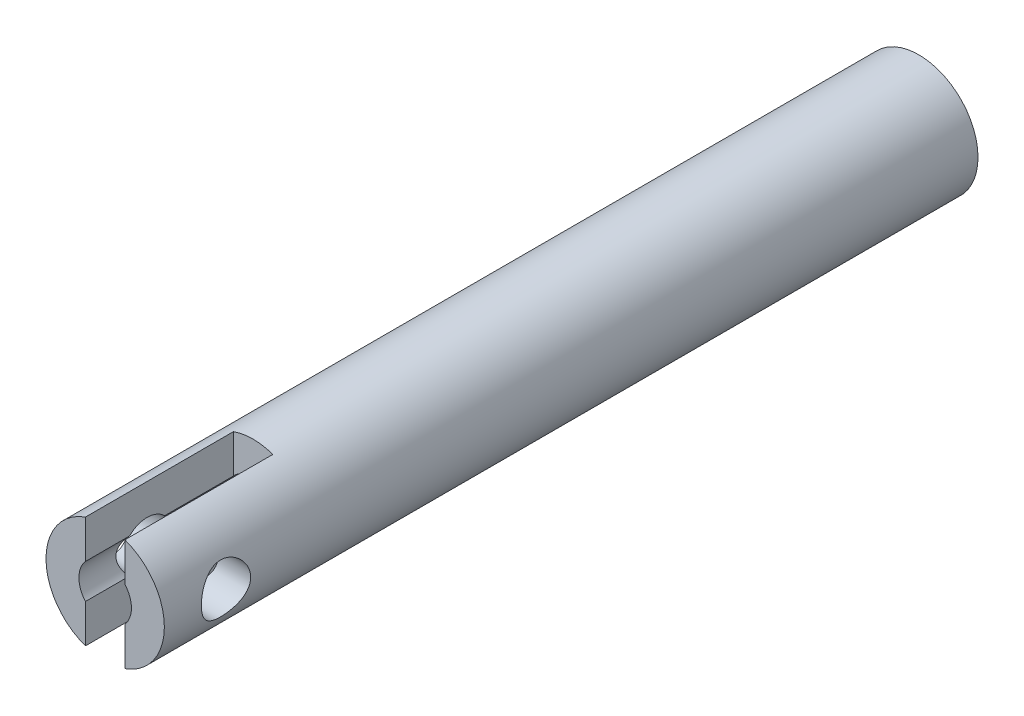
SolidWorks part; units mm, degrees
ref_plane "Front Plane" through (0, 0, 0) normal (0, 0, 1) x (1, 0, 0)
ref_plane "Top Plane" through (0, 0, 0) normal (0, 1, 0) x (1, 0, 0)
ref_plane "Right Plane" through (0, 0, 0) normal (1, 0, 0) x (0, 0, -1)
sketch "Sketch1" plane through (0, 0, 0) normal (0, 0, 1) x (1, 0, 0)
  circle A0 centre (0, 0) radius 3.048
  dimension "D1" = 6.096
extrude "Boss-Extrude1" add sketch "Sketch1" along normal blind 41.91
sketch "Sketch2" plane through (0, 0, 41.91) normal (0, 0, 1) x (1, 0, 0)
  line L0 (-1.016, -3.048) -> (0, 0) construction
  line L1 (-1.016, 3.048) -> (1.016, 3.048)
  line L2 (-1.016, 3.048) -> (-1.016, -3.048)
  line L3 (-1.016, -3.048) -> (1.016, -3.048)
  line L4 (1.016, 3.048) -> (1.016, -3.048)
  line L5 (0, 0) -> (1.016, 3.048) construction
  line L6 (1.016, 3.048) -> (1.0322, 3.0732)
  circle A0 centre (0, 0) radius 3.048 construction
  circle M1 centre (0, 0) radius 3.048
  dimension "D1" = 2.032
extrude "Cut-Extrude1" cut sketch "Sketch2" against normal blind 7.62 contours L4 L2 M1
sketch "Sketch3" plane through (-1.016, 0, 0) normal (1, 0, 0) x (0, 0, -1)
  line L0 (-41.91, 2.8737) -> (-41.91, -2.8737) construction
  line L1 (-41.91, 0) -> (-38.735, 0) construction
  circle A0 centre (-38.735, 0) radius 1.27
  dimension "D1" = 2.54
  dimension "D2" = 3.175
extrude "Cut-Extrude2" cut sketch "Sketch3" against normal through all both and the other way through all
sketch "Sketch8" plane through (0, 0, 0) normal (0, 0, -1) x (-1, 0, 0)
  circle A0 centre (0, 0) radius 1.1308
hole_wizard "#6-32 Tapped Hole1" positions "3DSketch5" profile "Sketch9" tap size "#6-32" standard "ANSI Inch" end condition through all
sketch3d "3DSketch5"
  line L0 (0, 0, 41.91) -> (0, 0, 0) construction
  point P0 (0, 0, 0)
  point P3 (0, 0, 0)
  point P7 (0, 0, 0)
  point P9 (0, 0, 0)
  point P11 (-6.4609, -0.9468, 0)
sketch "Sketch9" plane through (0, 0, 0) normal (1, 0, 0) x (0, 1, 0)
  line L0 (0, 0) -> (0, 41.91)
  line L1 (0, 41.91) -> (1.3525, 41.91)
  line L2 (1.3525, 41.91) -> (1.3525, 0)
  line L5 (1.3525, 0) -> (0, 0)
  line L11 (0, -6.35) -> (0, 107.95) construction
  dimension "Thru Tap Drill Dia." = 2.7051
  dimension "Thru Tap Drill Depth" = 41.91
cosmetic thread "Hole Thread1" parameters "D2"=3.5052
cosmetic thread "Hole Thread2" parameters "D2"=3.5052
cosmetic thread "Hole Thread3" parameters "D2"=3.5052
cosmetic thread "Hole Thread4" parameters "D2"=3.5052
cosmetic thread "Hole Thread5" parameters "D2"=3.5052
